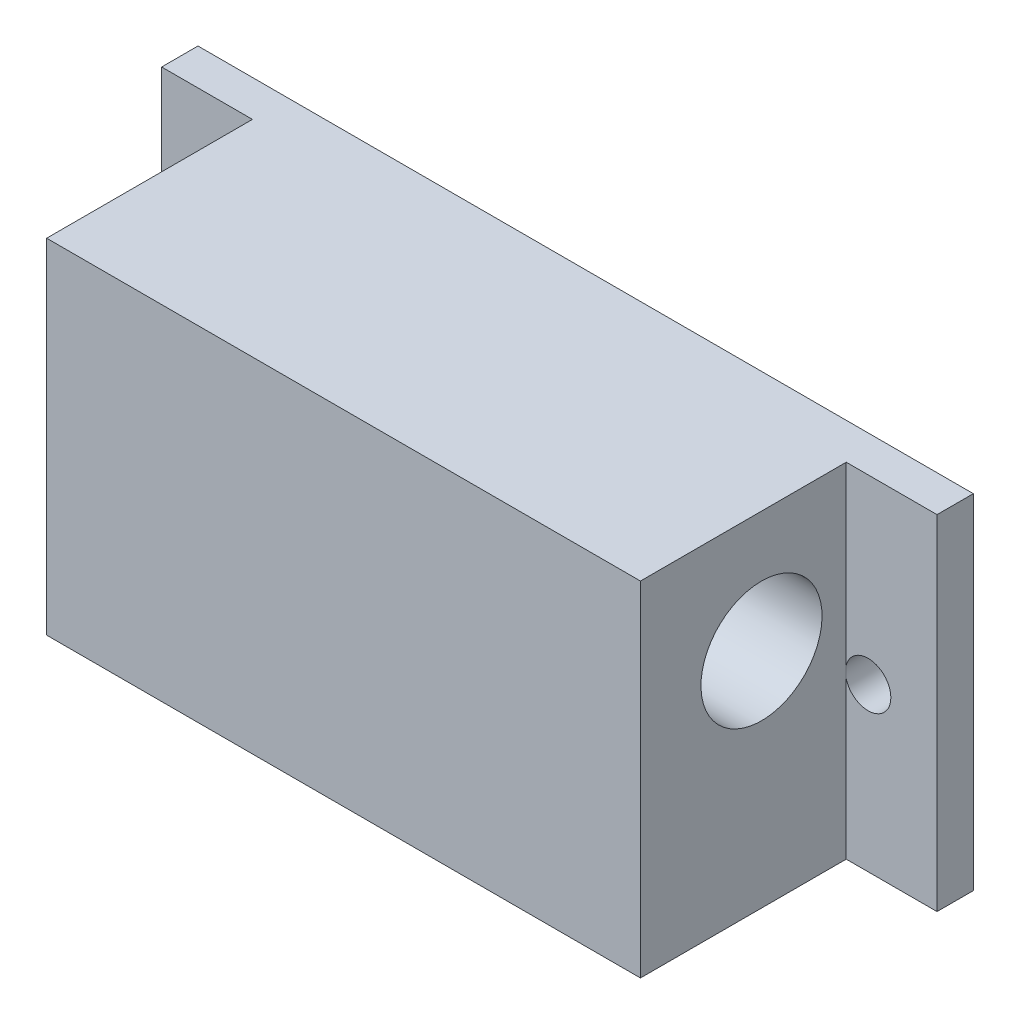
SolidWorks part; units mm, degrees
material "1060 Alloy"
ref_plane "Front" through (0, 0, 0) normal (0, 0, 1) x (1, 0, 0)
ref_plane "Top" through (0, 0, 0) normal (0, 1, 0) x (1, 0, 0)
ref_plane "Right" through (0, 0, 0) normal (1, 0, 0) x (0, 0, -1)
sketch "Sketch3" plane through (0, 0, 0) normal (0, 0, 1) x (1, 0, 0)
  line L0 (-0.127, -6.35) -> (30.1755, -6.35)
  line L1 (0, 0) -> (31.1484, 0)
  line L2 (0, 0) -> (0, -19.8376)
  line L3 (0, -19.8376) -> (31.1484, -19.8376)
  line L4 (31.1484, 0) -> (31.1484, -19.8376)
  line L5 (15.5742, -19.8376) -> (15.5742, 0) construction
  line L6 (15.5742, -6.35) -> (8.0621, -19.3614) construction
  line L15 (12.5496, -11.5887) -> (15.5742, -13.335) construction
  line L16 (15.5742, -6.35) -> (22.9274, -19.0862) construction
  circle A0 centre (15.5742, -6.35) radius 6.0492 construction
  point P14 (0, -6.35)
  point P17 (9.525, -6.35)
  point P19 (31.1484, -6.35)
  point P20 (7.7871, -19.8376)
  point P24 (23.3613, -19.8376)
  dimension "D2" = 6.35
  dimension "D6" = 3.4925
  dimension "D3" = 60
  dimension "D1" = 9.525
  dimension "D4" = 9.525
  dimension "D5" = 60
extrude "Boss-Extrude1" add sketch "Sketch3" along normal mid plane 12.7
sketch "Sketch4" plane through (0, 0, 0) normal (-1, 0, 0) x (0, 0, 1)
  circle A0 centre (0, -6.35) radius 3.175
  dimension "D1" = 6.35
extrude "Cut-Extrude1" cut sketch "Sketch4" against normal blind 9.525
ref_plane "Plane1" through (7.7871, -19.8376, 0) normal (-0.5, -0.866, 0) x (-0.866, 0.5, 0)
ref_plane "Mirror Plane" through (15.5742, 0, 0) normal (-1, 0, 0) x (0, 0, 1)
sketch "Sketch5" plane through (7.7871, -19.8376, 0) normal (-0.5, -0.866, 0) x (-0.866, 0.5, 0)
  circle A0 centre (0, 0) radius 3.175
  dimension "D1" = 6.35
extrude "Cut-Extrude5" cut sketch "Sketch5" against normal blind 9.525 and the other way up to next
sketch "Sketch6" plane through (0, 0, -6.35) normal (0, 0, -1) x (-1, 0, 0)
  circle A0 centre (-15.5742, -6.35) radius 3.175
  dimension "D1" = 6.35
extrude "Cut-Extrude6" cut sketch "Sketch6" against normal blind 9.525
mirror "Mirror1" about plane through (15.5742, 0, 0) normal (-1, 0, 0) of "Cut-Extrude1", "Cut-Extrude5"
sketch "Sketch8" plane through (31.1484, 0, 0) normal (1, 0, 0) x (0, 0, -1)
  line L0 (-6.35, -19.8376) -> (-6.35, 0) construction
  line L1 (-6.35, -18.034) -> (6.35, -18.034)
  line L2 (-6.35, -18.034) -> (-6.35, -19.8376)
  line L3 (-6.35, -19.8376) -> (6.35, -19.8376)
  line L4 (6.35, -18.034) -> (6.35, -19.8376)
  line L5 (-6.35, 0) -> (6.35, 0) construction
  dimension "D1" = 18.034
extrude "Cut-Extrude7" cut sketch "Sketch8" against normal through all
sketch "Sketch9" plane through (31.1484, 0, 0) normal (1, 0, 0) x (0, 0, -1)
  line L0 (6.35, -18.034) -> (-6.35, -18.034) construction
  line L1 (6.35, 0) -> (4.445, 0)
  line L2 (6.35, 0) -> (6.35, -18.034)
  line L3 (6.35, -18.034) -> (4.445, -18.034)
  line L4 (4.445, 0) -> (4.445, -18.034)
  dimension "D1" = 1.905
extrude "Boss-Extrude2" add sketch "Sketch9" along normal blind 4.7625
hole_wizard "3/32 (0.09375) Diameter Hole1" positions "Sketch10" profile "Sketch11" hole size "3/32" standard "ANSI Inch"
sketch "Sketch10" plane through (0, 0, -4.445) normal (0, 0, 1) x (1, 0, 0)
  line L0 (35.9109, 0) -> (31.1484, 0) construction
  point P0 (32.2971, -9.525)
  dimension "D1" = 9.525
sketch "Sketch11" plane through (32.2971, -9.525, -4.445) normal (1, 0, 0) x (0, -1, 0)
  line L0 (0, 0) -> (0, 1.906)
  line L1 (0, 1.906) -> (1.1906, 1.906)
  line L2 (1.1906, 1.906) -> (1.1906, 0)
  line L5 (1.1906, 0) -> (0, 0)
  line L11 (0, -6.35) -> (0, 107.95) construction
  dimension "Thru Hole Dia." = 2.3812
  dimension "Thru Hole Depth" = 1.906
mirror "Mirror2" about plane through (15.5742, 0, 0) normal (-1, 0, 0) of "Boss-Extrude2", "3/32 (0.09375) Diameter Hole1"
equation "\"truss_member_od\" = .25in"
equation "\"truss_member_id\"= 0in"
equation "\"truss_member_L1\" = 2.125in"
equation "\"connector_hole_depth\" = .375in"
equation "\"D1@Boss-Extrude1\"=\"truss_member_od\"*2"
equation "\"D6@Sketch3\"=\"truss_member_od\"/2*1.1"
equation "\"D1@Sketch4\"=\"truss_member_od\""
equation "\"D1@Cut-Extrude1\"=\"connector_hole_depth\""
equation "\"D1@Sketch3\"=\"connector_hole_depth\""
equation "\"D4@Sketch3\"=\"connector_hole_depth\""
equation "\"D1@Sketch5\"=\"truss_member_od\""
equation "\"D1@Cut-Extrude5\"=\"connector_hole_depth\""
equation "\"D1@Cut-Extrude6\"=\"connector_hole_depth\""
equation "\"D1@Sketch6\"=\"truss_member_od\""
